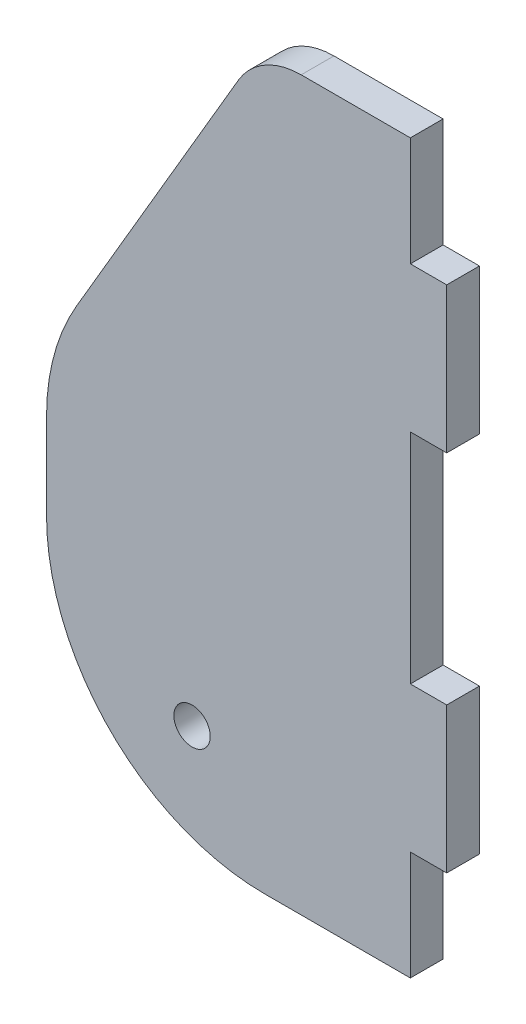
SolidWorks part; units mm, degrees
material "Balsa"
ref_plane "Front Plane" through (0, 0, 0) normal (0, 0, 1) x (1, 0, 0)
ref_plane "Top Plane" through (0, 0, 0) normal (0, 1, 0) x (1, 0, 0)
ref_plane "Right Plane" through (0, 0, 0) normal (1, 0, 0) x (0, 0, -1)
sketch "Sketch1" plane through (0, 0, 0) normal (0, 0, 1) x (1, 0, 0)
  line L0 (0, 0) -> (15, 0)
  line L1 (-15, -50) -> (15, -50)
  line L2 (-15, -50) -> (-15, 50)
  line L3 (-15, 50) -> (15, 50)
  line L4 (15, -50) -> (15, 50)
  line L5 (-15, -50) -> (15, 50) construction
  line L6 (-15, 50) -> (15, -50) construction
  line L7 (15, 35) -> (10, 35)
  line L8 (15, 35) -> (15, 15)
  line L9 (15, 15) -> (10, 15)
  line L10 (10, 35) -> (10, 15)
  line L11 (15, -35) -> (10, -35)
  line L12 (10, -35) -> (10, -15)
  line L13 (15, -15) -> (10, -15)
  line L14 (10, -50) -> (10, 50)
  point P0 (0, 0)
  dimension "D1" = 100
  dimension "D2" = 30
  dimension "D3" = 15
  dimension "D4" = 5
  dimension "D5" = 20
extrude "Boss-Extrude1" add sketch "Sketch1" along normal blind 4.5
fillet "Fillet1" radius 10 2 edges at (-15, -50, 2.25) (-15, 50, 2.25)
sketch "Sketch2" plane through (0, 0, 4.5) normal (0, 0, 1) x (1, 0, 0)
  line L0 (-40, 0) -> (-13.6303, 45.0515)
  line L1 (-40, 0) -> (-40, -50)
  line L2 (-40, -50) -> (-5, -50)
  line L3 (-5, -50) -> (10, -50) construction
  line L16 (-15, 40) -> (-15, -40)
  line L17 (-5, -50) -> (10, -50)
  line L18 (10, -50) -> (10, -35)
  line L19 (10, -35) -> (15, -35)
  line L20 (15, -35) -> (15, -15)
  line L21 (15, -15) -> (10, -15)
  line L22 (10, -15) -> (10, 15)
  line L23 (10, 15) -> (15, 15)
  line L24 (15, 15) -> (15, 35)
  line L25 (15, 35) -> (10, 35)
  line L26 (10, 35) -> (10, 50)
  line L27 (10, 50) -> (-5, 50)
  line L28 (-15, 40) -> (-15, -40)
  arc A0 (-5, 50) -> (-15, 40) centre (-5, 40) ccw construction
  arc A3 (-15, -40) -> (-5, -50) centre (-5, -40) ccw
  arc A4 (-5, 50) -> (-15, 40) centre (-5, 40) ccw
  arc A5 (-15, -40) -> (-5, -50) centre (-5, -40) ccw
  arc A6 (-13.6303, 45.0515) -> (-15, 40) centre (-5, 40) ccw
  dimension "D1" = 40
  dimension "D2" = 0
extrude "Boss-Extrude2" add sketch "Sketch2" against normal blind 4.5
fillet "Fillet2" radius 30 2 edges at (-40, -50, 2.25) (-40, 0, 2.25)
sketch "Sketch3" plane through (0, 0, 4.5) normal (0, 0, 1) x (1, 0, 0)
  line L0 (15, -35) -> (10, -35) construction
  circle A0 centre (-20, -35) radius 2.5
  dimension "D1" = 5
  dimension "20" = 20
extrude "Cut-Extrude1" cut sketch "Sketch3" against normal blind 5
